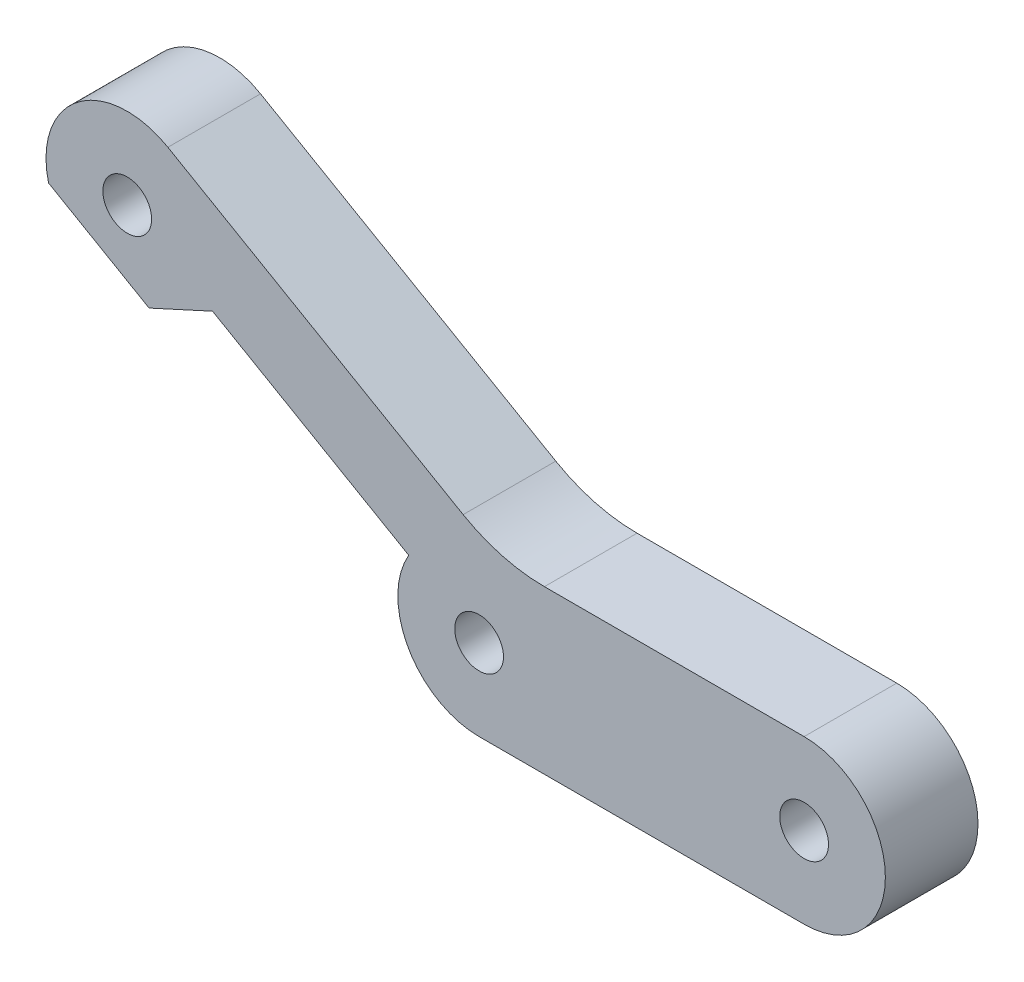
SolidWorks part; units mm, degrees
ref_plane "정면" through (0, 0, 0) normal (0, 0, 1) x (1, 0, 0)
ref_plane "윗면" through (0, 0, 0) normal (0, 1, 0) x (1, 0, 0)
ref_plane "우측면" through (0, 0, 0) normal (1, 0, 0) x (0, 0, -1)
sketch "스케치1" plane through (0, 0, 0) normal (0, 0, 1) x (1, 0, 0)
  line L0 (-10, 0) -> (10, 0) construction
  line L1 (-10, -5) -> (10, -5)
  line L2 (-5.9808, 5) -> (10, 5)
  line L3 (-10, 0) -> (-11.299, 0.75)
  line L4 (-10.9808, 6.3397) -> (-29.1506, 16.8301)
  line L5 (-14.3301, 2.5) -> (-26.4006, 9.4689)
  line L6 (-33.4006, 9.4689) -> (-36.493, 11.2543)
  line L7 (-33.4006, 9.4689) -> (-30.3083, 7.6836)
  line L8 (-30.3083, 7.6836) -> (-26.4006, 9.4689)
  line L9 (-7.5, 4.3301) -> (-29.1506, 16.8301) construction
  line L10 (-10, 0) -> (-31.6506, 12.5) construction
  arc A0 (-14.3301, 2.5) -> (-10, -5) centre (-10, 0) ccw
  arc A1 (10, -5) -> (10, 5) centre (10, 0) ccw
  circle A2 centre (-10, 0) radius 1.5
  circle A3 centre (10, 0) radius 1.5
  circle A4 centre (-31.6506, 12.5) radius 1.5
  arc A6 (-29.1506, 16.8301) -> (-36.493, 11.2543) centre (-31.6506, 12.5) ccw
  arc A7 (-5.9808, 5) -> (-10.9808, 6.3397) centre (-5.9808, 15) cw
  point P3 (0, 0)
  dimension "D1" = 150
extrude "보스-돌출1" add sketch "스케치1" along normal blind 5.7 contours L2 A7 L4 A6 L6 L7 L8 L5 A0 L1 A1 A2 A3 A4
